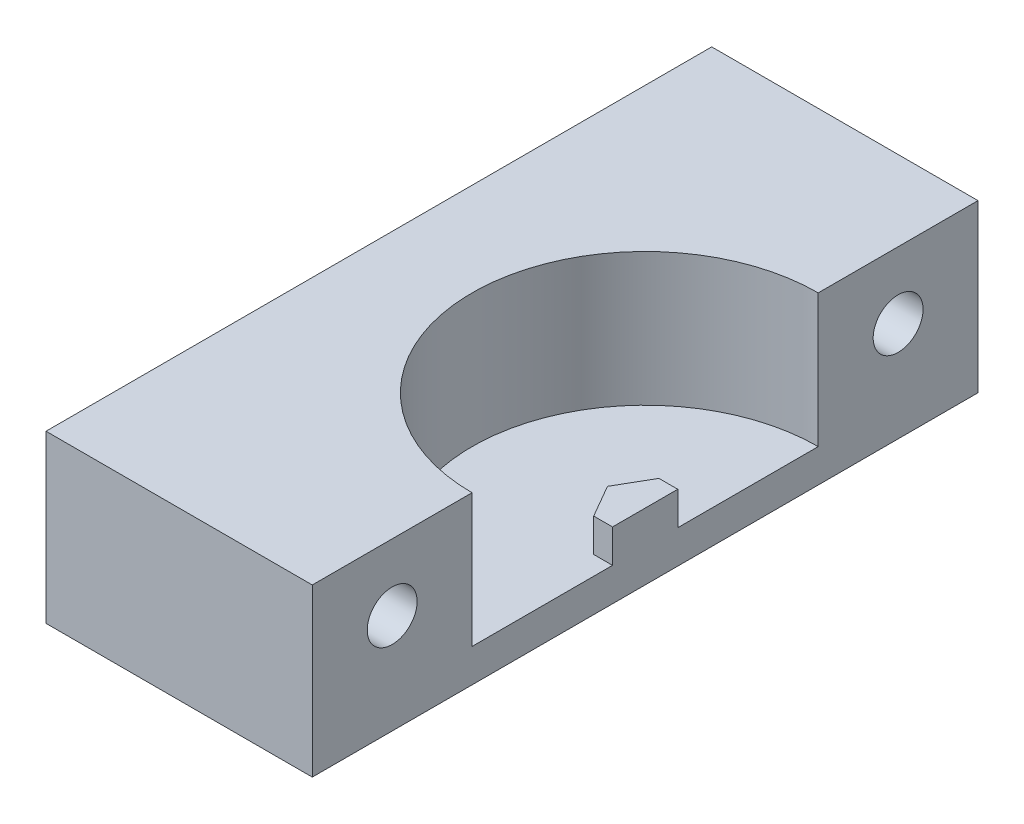
SolidWorks part; units mm, degrees
ref_plane "Front Plane" through (0, 0, 0) normal (0, 0, 1) x (1, 0, 0)
ref_plane "Top Plane" through (0, 0, 0) normal (0, 1, 0) x (1, 0, 0)
ref_plane "Right Plane" through (0, 0, 0) normal (1, 0, 0) x (0, 0, -1)
sketch "Sketch1" plane through (0, 0, 0) normal (0, 1, 0) x (1, 0, 0)
  line L0 (0, 33.02) -> (0, 63.5)
  line L1 (0, 63.5) -> (-50.8, 63.5)
  line L2 (-50.8, 63.5) -> (-50.8, -63.5)
  line L3 (-50.8, -63.5) -> (0, -63.5)
  line L4 (0, -63.5) -> (0, -33.02)
  arc A0 (0, 33.02) -> (0, -33.02) centre (0, 0) ccw
  point P6 (-50.8, 0)
  point P10 (0, 0)
  dimension "D1" = 127
  dimension "D2" = 66.04
  dimension "D3" = 50.8
extrude "Boss-Extrude1" add sketch "Sketch1" along normal blind 25.4
sketch "Sketch2" plane through (0, 0, 0) normal (0, -1, 0) x (1, 0, 0)
  line L1 (-50.8, 63.5) -> (0, 63.5)
  line L2 (-50.8, 63.5) -> (-50.8, -63.5)
  line L3 (-50.8, -63.5) -> (0, -63.5)
  line L4 (0, 63.5) -> (0, -63.5)
extrude "Boss-Extrude2" add sketch "Sketch2" along normal blind 6.35
sketch "Sketch3" plane through (0, 0, 0) normal (1, 0, 0) x (0, 0, -1)
  line L0 (0, 0) -> (0, 25.4) construction
  line L1 (33.02, 25.4) -> (-33.02, 25.4) construction
  line L2 (-63.5, 25.4) -> (-33.02, 25.4) construction
  line L3 (-33.02, 25.4) -> (-33.02, 0) construction
  circle A0 centre (-48.26, 12.7) radius 4.7625
  circle A1 centre (48.26, 12.7) radius 4.7625
  dimension "D1" = 12.7
  dimension "D2" = 9.525
  dimension "D3" = 15.24
extrude "Cut-Extrude1" cut sketch "Sketch3" against normal through all
sketch "Sketch4" plane through (0, 0, 0) normal (0, 1, 0) x (1, 0, 0)
  line L0 (0, 33.02) -> (0, -33.02) construction
  line L1 (-3.5929, 6.223) -> (-7.1857, 0)
  line L2 (-7.1857, 0) -> (-3.5929, -6.223)
  line L3 (-3.5929, -6.223) -> (0, -6.223)
  line L6 (0, 6.223) -> (-3.5929, 6.223)
  line L7 (0, 6.223) -> (0, -6.223)
  line L9 (3.5929, -6.223) -> (5.3893, -3.1115) [skipped]
  line L10 (5.3893, 3.1115) -> (3.5929, 6.223) [skipped]
  arc A0 (0, 6.223) -> (0, -6.223) centre (0, 0) ccw construction
  dimension "D1" = 12.446
extrude "Boss-Extrude3" add sketch "Sketch4" along normal blind 6.35
